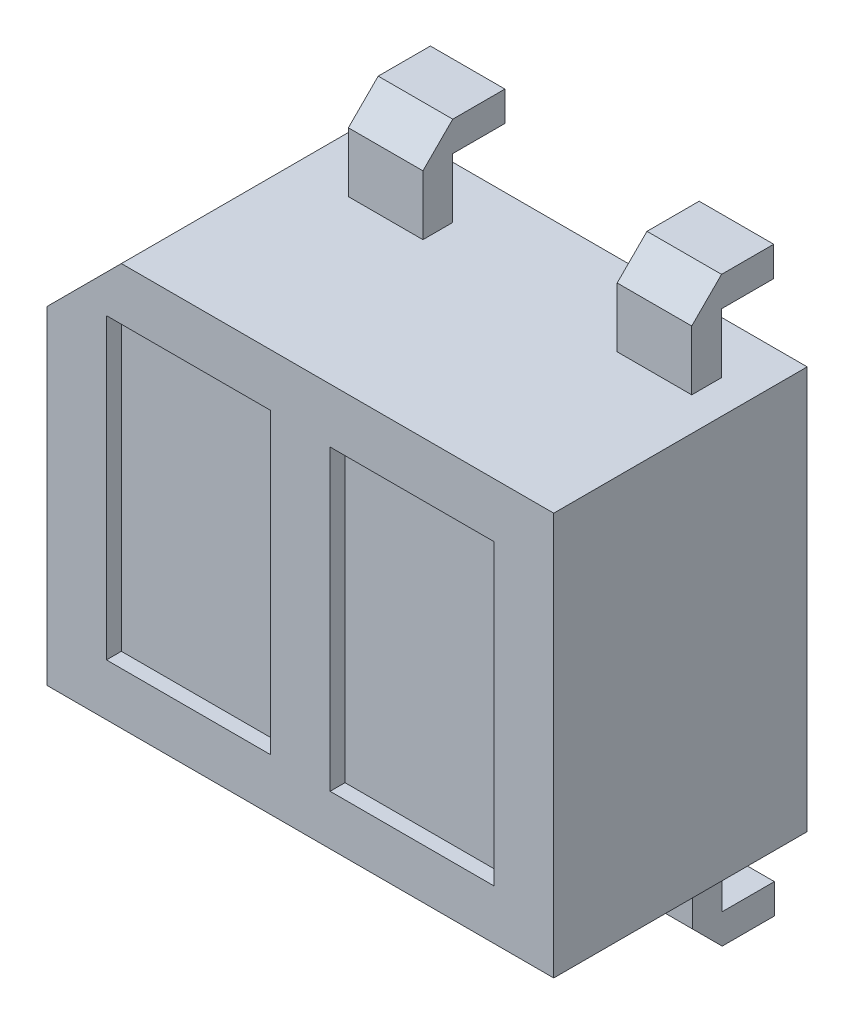
SolidWorks part; units mm, degrees
ref_plane "Přední rovina" through (0, 0, 0) normal (0, 0, 1) x (1, 0, 0)
ref_plane "Horní rovina" through (0, 0, 0) normal (0, 1, 0) x (1, 0, 0)
ref_plane "Pravá rovina" through (0, 0, 0) normal (1, 0, 0) x (0, 0, -1)
sketch "Skica1" plane through (0, 0, 0) normal (0, 0, 1) x (1, 0, 0)
  line L1 (-1.7, -1.35) -> (1.7, -1.35)
  line L2 (-1.7, -1.35) -> (-1.7, 1.35)
  line L3 (-1.7, 1.35) -> (1.7, 1.35)
  line L4 (1.7, -1.35) -> (1.7, 1.35)
  line L5 (-1.7, -1.35) -> (1.7, 1.35) construction
  line L6 (-1.7, 1.35) -> (1.7, -1.35) construction
  point P0 (0, 0)
  dimension "D1" = 3.4
  dimension "D2" = 2.7
extrude "Přidat vysunutím1" add sketch "Skica1" along normal blind 1.7
sketch "Skica2" plane through (0, 0, 1.7) normal (0, 0, 1) x (1, 0, 0)
  line L0 (-1.7, 1.35) -> (-1.7, -1.35) construction
  line L1 (1.7, -1.35) -> (1.7, 1.35) construction
  line L11 (-1.3, -1.0024) -> (-0.2, -1.0024)
  line L12 (-1.3, -1.0024) -> (-1.3, 0.9976)
  line L13 (-1.3, 0.9976) -> (-0.2, 0.9976)
  line L14 (-0.2, -1.0024) -> (-0.2, 0.9976)
  line L15 (0.2, 0.9845) -> (1.3, 0.9845)
  line L16 (0.2, 0.9845) -> (0.2, -1.0155)
  line L17 (0.2, -1.0155) -> (1.3, -1.0155)
  line L18 (1.3, 0.9845) -> (1.3, -1.0155)
  dimension "D1" = 0.4
  dimension "D2" = 0.4
  dimension "D3" = 1.1
  dimension "D4" = 1.1
  dimension "D5" = 0.4
  dimension "D6" = 2
  dimension "D7" = 2
extrude "Odebrat vysunutím2" cut sketch "Skica2" against normal blind 0.1
ref_plane "Rovina2" through (-1.7, 1.35, 1.7) normal (-1, 0, 0) x (0, 0, 1)
sketch "Skica4" plane through (0, 0, 1.7) normal (0, 0, 1) x (1, 0, 0)
  line L0 (-1.7, 0.85) -> (-1.2, 1.35)
  line L1 (-1.7, 1.35) -> (-1.7, -1.35) construction
  line L2 (1.7, 1.35) -> (-1.7, 1.35) construction
  line L3 (-1.2, 1.35) -> (-1.7, 1.35)
  line L4 (-1.7, 1.35) -> (-1.7, 0.85)
  dimension "D1" = 0.5
  dimension "D2" = 0.5
extrude "Odebrat vysunutím4" cut sketch "Skica4" against normal through all
sketch "Skica5" plane through (0, 1.35, 0) normal (0, 1, 0) x (1, 0, 0)
  line L0 (1.7, 0) -> (-1.2, 0) construction
  line L1 (1.4756, -0.35) -> (0.9756, -0.35)
  line L2 (1.4756, -0.35) -> (1.4756, -0.55)
  line L3 (1.4756, -0.55) -> (0.9756, -0.55)
  line L4 (0.9756, -0.35) -> (0.9756, -0.55)
  line L5 (-0.3273, -0.35) -> (-0.8273, -0.35)
  line L6 (-0.3273, -0.35) -> (-0.3273, -0.55)
  line L7 (-0.3273, -0.55) -> (-0.8273, -0.55)
  line L8 (-0.8273, -0.35) -> (-0.8273, -0.55)
  dimension "D1" = 0.5
  dimension "D2" = 0.5
  dimension "D3" = 0.55
  dimension "D4" = 0.55
  dimension "D5" = 0.2
  dimension "D6" = 0.2
extrude "Přidat vysunutím2" add sketch "Skica5" along normal blind 0.6
sketch "Skica6" plane through (0, 0, 0.35) normal (0, 0, -1) x (-1, 0, 0)
  line L0 (0.8273, 1.95) -> (0.8273, 1.35) construction
  line L1 (-0.9756, 1.95) -> (-0.9756, 1.35) construction
  line L2 (-1.4756, 1.95) -> (-0.9756, 1.95)
  line L3 (-1.4756, 1.95) -> (-1.4756, 1.75)
  line L4 (-1.4756, 1.75) -> (-0.9756, 1.75)
  line L6 (0.3273, 1.95) -> (0.8273, 1.95)
  line L7 (0.3273, 1.95) -> (0.3273, 1.75)
  line L8 (0.3273, 1.75) -> (0.8273, 1.75)
  line L9 (0.8273, 1.95) -> (0.8273, 1.75)
  line L10 (-0.9756, 1.95) -> (-0.9756, 1.75)
  dimension "D1" = 0.2
  dimension "D2" = 0.2
extrude "Přidat vysunutím3" add sketch "Skica6" along normal up to vertex (0.35 mm away)
chamfer "Zkosení2" distance 0.2 angle 45 2 edges at (-0.5773, 1.95, 0.55) (1.2256, 1.95, 0.55)
sketch "Skica8" plane through (0, -1.35, 0) normal (0, -1, 0) x (1, 0, 0)
  line L0 (1.7, 1.7) -> (1.7, 0) construction
  line L1 (1.48, 0.35) -> (0.98, 0.35)
  line L2 (1.48, 0.35) -> (1.48, 0.55)
  line L3 (1.48, 0.55) -> (0.98, 0.55)
  line L4 (0.98, 0.35) -> (0.98, 0.55)
  line L5 (-0.32, 0.35) -> (-0.82, 0.35)
  line L6 (-0.32, 0.35) -> (-0.32, 0.55)
  line L7 (-0.32, 0.55) -> (-0.82, 0.55)
  line L8 (-0.82, 0.35) -> (-0.82, 0.55)
  line L9 (-1.7, 0) -> (1.7, 0) construction
  dimension "D1" = 0.2
  dimension "D2" = 0.5
  dimension "D3" = 0.22
  dimension "D4" = 1.3
  dimension "D5" = 0.55
  dimension "D6" = 0.55
extrude "Přidat vysunutím4" add sketch "Skica8" along normal blind 0.6
sketch "Skica9" plane through (0, 0, 0.35) normal (0, 0, -1) x (-1, 0, 0)
  line L0 (-1.48, -1.95) -> (-1.48, -1.35) construction
  line L1 (-0.98, -1.95) -> (-1.48, -1.95)
  line L2 (-0.98, -1.95) -> (-0.98, -1.75)
  line L3 (-0.98, -1.75) -> (-1.48, -1.75)
  line L4 (-1.48, -1.95) -> (-1.48, -1.75)
  line L5 (0.32, -1.95) -> (0.32, -1.35) construction
  line L6 (0.82, -1.95) -> (0.32, -1.95)
  line L7 (0.82, -1.95) -> (0.82, -1.75)
  line L8 (0.82, -1.75) -> (0.32, -1.75)
  line L9 (0.32, -1.95) -> (0.32, -1.75)
  dimension "D1" = 0.2
extrude "Přidat vysunutím5" add sketch "Skica9" along normal up to vertex (0.35 mm away)
chamfer "Zkosení3" distance 0.2 angle 45 2 edges at (1.23, -1.95, 0.55) (-0.57, -1.95, 0.55)
